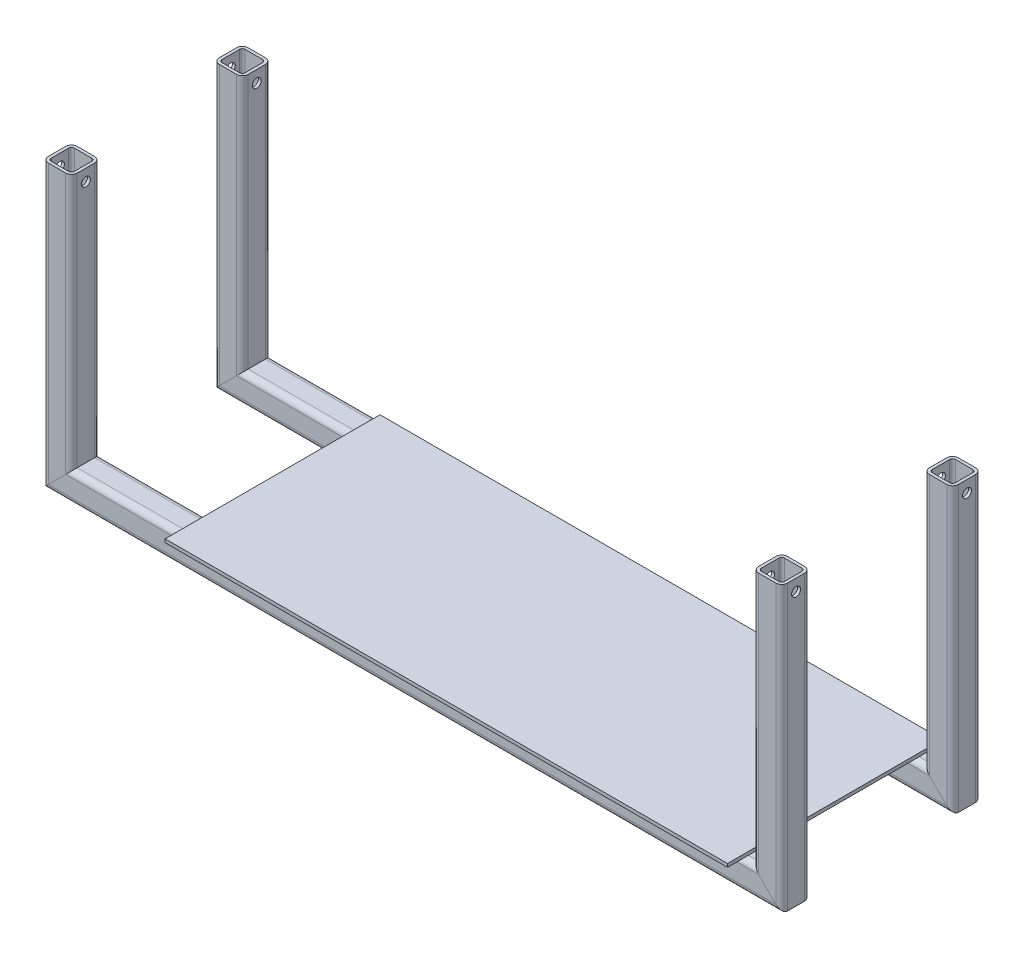
SolidWorks part; units mm, degrees
ref_plane "Alzado" through (0, 0, 0) normal (0, 0, 1) x (1, 0, 0)
ref_plane "Planta" through (0, 0, 0) normal (0, 1, 0) x (1, 0, 0)
ref_plane "Vista lateral" through (0, 0, 0) normal (1, 0, 0) x (0, 0, -1)
sketch3d "3DSketch1"
  line L0 (-246.25, 0, 59.25) -> (246.25, 0, 59.25)
  line L1 (-246.25, 0, 59.25) -> (-246.25, 187, 59.25)
  line L2 (246.25, 0, 59.25) -> (246.25, 187, 59.25)
  line L3 (246.25, 0, -59.25) -> (246.25, 187, -59.25)
  line L4 (-246.25, 0, -59.25) -> (246.25, 0, -59.25)
  line L5 (-246.25, 0, -59.25) -> (-246.25, 187, -59.25)
  dimension "D1" = 492.5
  dimension "D2" = 59.25
  dimension "D3" = 246.25
  dimension "D4" = 187
other "Square tube 20 X 20 X 2(1)"
ref_plane "Plane1" through (-246.25, 0, 59.25) normal (0, 1, 0) x (1, 0, 0)
sketch "Sketch1" plane through (-246.25, 0, 59.25) normal (0, 1, 0) x (1, 0, 0)
  line L0 (-6, -8) -> (6, -8)
  line L1 (-8, -6) -> (-8, 6)
  line L2 (6, 8) -> (-6, 8)
  line L3 (8, 6) -> (8, -6)
  line L4 (-6, -10) -> (6, -10)
  line L5 (-10, -6) -> (-10, 6)
  line L6 (6, 10) -> (-6, 10)
  line L7 (10, 6) -> (10, -6)
  arc A0 (10, 6) -> (6, 10) centre (6, 6) ccw
  arc A1 (6, -10) -> (10, -6) centre (6, -6) ccw
  arc A2 (-10, -6) -> (-6, -10) centre (-6, -6) ccw
  arc A3 (-6, 10) -> (-10, 6) centre (-6, 6) ccw
  arc A4 (-6, 8) -> (-8, 6) centre (-6, 6) ccw
  arc A5 (8, 6) -> (6, 8) centre (6, 6) ccw
  arc A6 (6, -8) -> (8, -6) centre (6, -6) ccw
  arc A7 (-8, -6) -> (-6, -8) centre (-6, -6) ccw
  point P0 (-10, 0)
  point P1 (10, 0)
  point P2 (0, 10)
  point P3 (0, -10)
  point P4 (0, 0)
  point P5 (-10, -10)
  point P6 (10, -10)
  point P7 (10, 10)
  point P8 (-10, 10)
  point P33 (0, 0)
  dimension "D1" = 4
  dimension "Thickness" = 2
  dimension "V_leg" = 20
sketch "Sketch2" plane through (0, 10, 0) normal (0, 1, 0) x (1, 0, 0)
  line L0 (-240.25, 69.25) -> (240.25, 69.25) construction
  line L1 (-160.8082, 69.25) -> (229.1918, 69.25)
  line L2 (-160.8082, 69.25) -> (-160.8082, -79.75)
  line L3 (-160.8082, -79.75) -> (229.1918, -79.75)
  line L4 (229.1918, 69.25) -> (229.1918, -79.75)
  dimension "D1" = 390
  dimension "D2" = 149
extrude "Boss-Extrude1" add sketch "Sketch2" along normal blind 2.3 separate body
sketch "Sketch3" plane through (0, 0, 0) normal (1, 0, 0) x (0, 0, -1)
  line L0 (59.25, 0) -> (59.25, 187) construction
  line L1 (65.25, 187) -> (53.25, 187) construction
  line L2 (0, 108.35) -> (0, -108.35) construction
  circle A0 centre (59.25, 178.8) radius 3.1
  circle A1 centre (-59.25, 178.8) radius 3.1
  dimension "D1" = 6.2
  dimension "D2" = 8.2
extrude "Cut-Extrude1" cut sketch "Sketch3" against normal blind 10000
sketch "Sketch4" plane through (0, 0, 0) normal (1, 0, 0) x (0, 0, -1)
  line L0 (59.25, 0) -> (59.25, 187) construction
  line L1 (65.25, 187) -> (53.25, 187) construction
  line L2 (0, 108.35) -> (0, -108.35) construction
  circle A0 centre (59.25, 178.8) radius 3.1
  circle A1 centre (-59.25, 178.8) radius 3.1
  dimension "D1" = 6.2
  dimension "D2" = 8.2
extrude "Cut-Extrude2" cut sketch "Sketch4" along normal blind 10000
